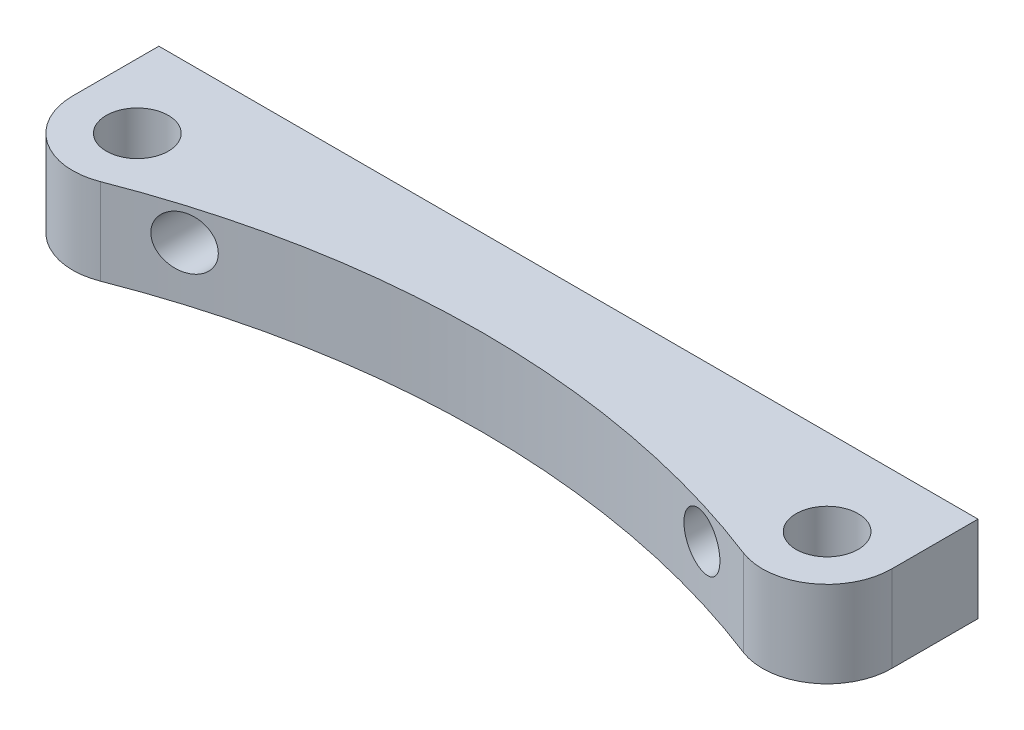
SolidWorks part; units mm, degrees
ref_plane "Front Plane" through (0, 0, 0) normal (0, 0, 1) x (1, 0, 0)
ref_plane "Top Plane" through (0, 0, 0) normal (0, 1, 0) x (1, 0, 0)
ref_plane "Right Plane" through (0, 0, 0) normal (1, 0, 0) x (0, 0, -1)
sketch "Sketch1" plane through (0, 0, 0) normal (0, 1, 0) x (1, 0, 0)
  line L0 (0, 0) -> (50.8, 0) construction
  line L4 (-4.7625, 6.35) -> (-4.7625, 0)
  line L5 (55.5625, 0) -> (55.5625, 6.35)
  line L7 (-4.7625, 6.35) -> (55.5625, 6.35)
  arc A0 (-4.7625, 0) -> (1.7253, -4.439) centre (0, 0) ccw
  arc A1 (49.0747, -4.439) -> (55.5625, 0) centre (50.8, 0) ccw
  circle A2 centre (0, 0) radius 2.286
  circle A3 centre (50.8, 0) radius 2.286
  arc A4 (1.7253, -4.439) -> (49.0747, -4.439) centre (25.4, -65.3521) cw
  point P3 (25.4, 0)
  point P4 (-4.4664, 1.653)
  dimension "D3" = 4.572
  dimension "D4" = 4.7625
  dimension "D1" = 6.35
  dimension "D2" = 50.8
  dimension "D5" = 6.35
extrude "Boss-Extrude1" add sketch "Sketch1" along normal blind 6.35
sketch "Sketch2" plane through (0, 0, -6.35) normal (0, 0, -1) x (-1, 0, 0)
  circle A4 centre (-6.35, 3.9688) radius 1.905
  circle A5 centre (-44.45, 3.9688) radius 1.905
  dimension "D1" = 3.81
extrude "Cut-Extrude1" cut sketch "Sketch2" against normal up to next
